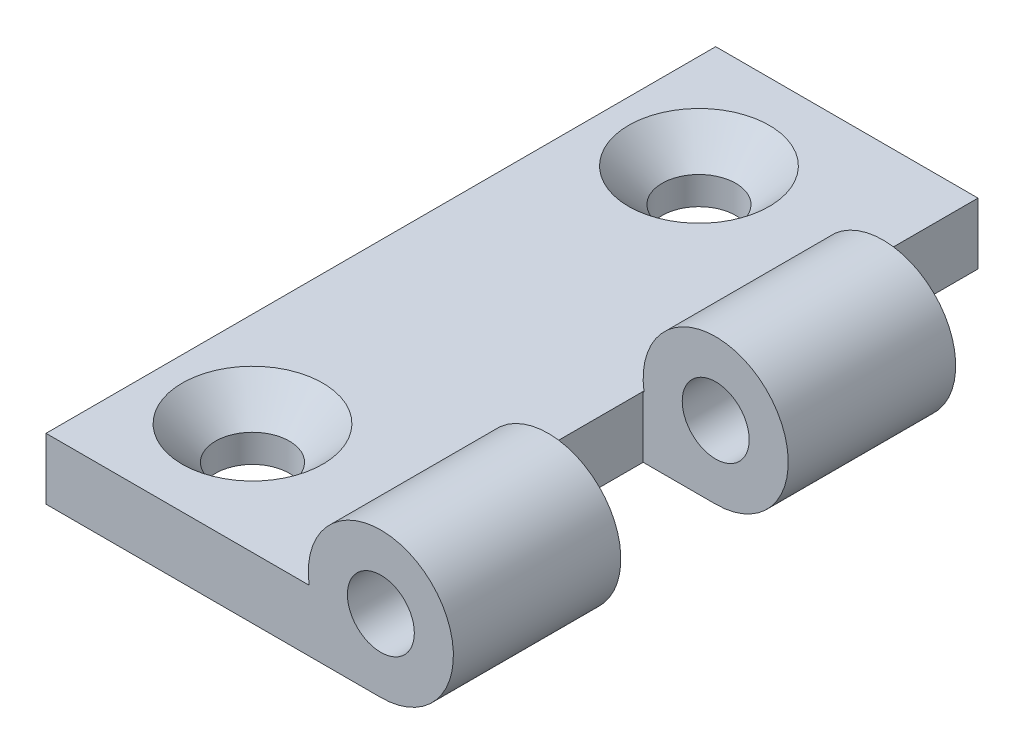
SolidWorks part; units mm, degrees
ref_plane "Front Plane" through (0, 0, 0) normal (0, 0, 1) x (1, 0, 0)
ref_plane "Top Plane" through (0, 0, 0) normal (0, 1, 0) x (1, 0, 0)
ref_plane "Right Plane" through (0, 0, 0) normal (1, 0, 0) x (0, 0, -1)
sketch "Sketch1" plane through (0, 0, 0) normal (0, 0, 1) x (1, 0, 0)
  line L0 (0, -6.5) -> (-30, -6.5)
  line L1 (-30, -6.5) -> (-30, -1)
  line L2 (-30, -1) -> (-6.4226, -1)
  circle A0 centre (0, 0) radius 6.5
  circle A1 centre (0, 0) radius 3
  dimension "D1" = 13
  dimension "D2" = 6
  dimension "D3" = 5.5
  dimension "D4" = 30
extrude "Boss-Extrude1" add sketch "Sketch1" along normal mid plane 60 contours A0 L2 L1 L0 | A0 A1
sketch "Sketch2" plane through (0, -1, 0) normal (0, 1, 0) x (1, 0, 0)
  line L0 (-21.5, 20) -> (-21.5, -20) construction
  point P0 (-21.5, 20)
  point P1 (-21.5, -20)
  point P2 (-21.5, 0)
  dimension "D1" = 40
  dimension "D2" = 21.5
hole_wizard "CSK for M6 Countersunk Flat Head Screw1" positions "Sketch2" profile "Sketch3" countersink size "M6" standard "ISO" end condition through all
sketch "Sketch3" plane through (-21.5, -1, -20) normal (1, 0, 0) x (0, 0, 1)
  line L0 (0, 0) -> (0, 5.5)
  line L1 (0, 5.5) -> (3.3, 5.5)
  line L2 (3.3, 5.5) -> (3.3, 3)
  line L3 (3.3, 3) -> (6.3, 0)
  line L5 (6.3, 0) -> (0, 0)
  line L6 (-3.3, 3) -> (-6.3, 0) construction
  line L11 (0, -6.35) -> (0, 107.95) construction
  dimension "Thru Hole Dia." = 6.6
  dimension "Thru Hole Depth" = 5.5
  dimension "Near C'Sink Dia." = 12.6
  dimension "Near C'Sink Angle" = 90
sketch "Sketch4" plane through (0, 0, 0) normal (0, 1, 0) x (1, 0, 0)
  line L0 (6.5, 30) -> (-6.5, 30) construction
  line L1 (6.5, 30) -> (-6.5, 30)
  line L2 (6.5, 30) -> (6.5, 15)
  line L3 (6.5, 15) -> (-6.5, 15)
  line L4 (-6.5, 30) -> (-6.5, 15)
  line L5 (-6.5, 30) -> (-6.5, -30) construction
  line L6 (6.5, -30) -> (6.5, 30) construction
  line L8 (6.5, 0) -> (-6.5, 0)
  line L9 (6.5, 0) -> (6.5, -15)
  line L10 (6.5, -15) -> (-6.5, -15)
  line L11 (-6.5, 0) -> (-6.5, -15)
  dimension "D1" = 15
  dimension "D2" = 15
  dimension "D3" = 15
extrude "Cut-Extrude1" cut sketch "Sketch4" against normal through all both and the other way through all
